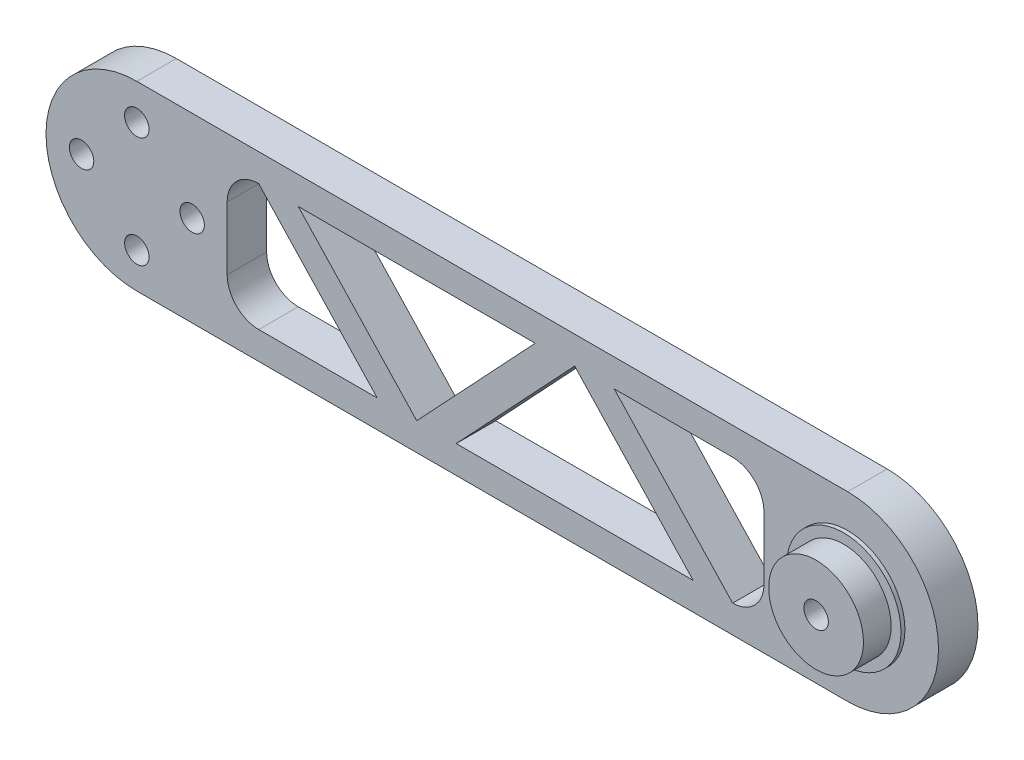
SolidWorks part; units mm, degrees
ref_plane "前视基准面" through (0, 0, 0) normal (0, 0, 1) x (1, 0, 0)
ref_plane "上视基准面" through (0, 0, 0) normal (0, 1, 0) x (1, 0, 0)
ref_plane "右视基准面" through (0, 0, 0) normal (1, 0, 0) x (0, 0, -1)
other "Configuration Table"
sketch "Sketch2" plane through (0, 0, 0) normal (0, 0, 1) x (1, 0, 0)
  line L0 (0, 0) -> (90, 0) construction
  line L1 (0, 11.5) -> (90, 11.5)
  line L2 (0, -11.5) -> (90, -11.5)
  arc A0 (0, 11.5) -> (0, -11.5) centre (0, 0) ccw
  arc A1 (90, -11.5) -> (90, 11.5) centre (90, 0) ccw
  circle A2 centre (90, 0) radius 6
  point P3 (45, 0)
extrude "Boss-Extrude1" add sketch "Sketch2" against normal blind 5 contours L1 A1 L2 A0
sketch "Sketch11" plane through (0, 0, 0) normal (0, 0, 1) x (1, 0, 0)
  circle A0 centre (90, 0) radius 7.25
extrude "Boss-Extrude3" add sketch "Sketch11" along normal blind 0.5 contours A0
sketch "Sketch12" plane through (0, 0, 0.5) normal (0, 0, 1) x (1, 0, 0)
  circle A0 centre (90, 0) radius 6
extrude "Boss-Extrude4" add sketch "Sketch12" along normal blind 3.5 contours A0
sketch "Sketch13" plane through (0, 0, 4) normal (0, 0, 1) x (1, 0, 0)
  circle A0 centre (90, 0) radius 1.55
extrude "Cut-Extrude1" cut sketch "Sketch13" against normal blind 20.5
sketch "Sketch14" plane through (0, 0, -5) normal (0, 0, -1) x (-1, 0, 0)
  line L1 (-93.2136, -0.3551) -> (-91.2993, -2.9606)
  line L2 (-91.2993, -2.9606) -> (-88.0857, -2.6055)
  line L3 (-88.0857, -2.6055) -> (-86.7864, 0.3551)
  line L4 (-86.7864, 0.3551) -> (-88.7007, 2.9606)
  line L5 (-88.7007, 2.9606) -> (-91.9143, 2.6055)
  line L6 (-91.9143, 2.6055) -> (-93.2136, -0.3551)
  circle A0 centre (-90, 0) radius 2.8 construction
extrude "Cut-Extrude2" cut sketch "Sketch14" against normal blind 2.6 contours L4 L5 L6 L1 L2 L3
sketch "Sketch16" plane through (0, 0, -5) normal (0, 0, -1) x (-1, 0, 0)
  circle A0 centre (0, 0) radius 2.85
extrude "Cut-Extrude3" cut sketch "Sketch16" against normal blind 3.02 contours A0
sketch "Sketch17" plane through (0, 0, 0) normal (0, 0, 1) x (1, 0, 0)
  circle A0 centre (0, 7) radius 1.55
  circle A1 centre (0, -7) radius 1.55
  circle A2 centre (-7, 0) radius 1.55
  circle A3 centre (7, 0) radius 1.55
  dimension "D1" = 14
  dimension "D2" = 14
  dimension "D3" = 7
  dimension "D4" = 7
extrude "Cut-Extrude4" cut sketch "Sketch17" against normal blind 10.02 contours A3 | A1 | A2 | A0
sketch "Sketch18" plane through (0, 0, 0) normal (0, 0, 1) x (1, 0, 0)
  line L0 (0, 11.5) -> (90, 11.5) construction
  line L1 (15.4373, 8) -> (75.3963, 8)
  line L2 (11.4373, 4) -> (11.4373, -4)
  line L3 (15.4373, -8) -> (75.4373, -8)
  line L4 (79.3963, 4) -> (79.3963, -4.0002)
  line L5 (0, -11.5) -> (90, -11.5) construction
  line L6 (15.4373, 8) -> (20.4373, 8)
  line L7 (15.4373, 8) -> (30.4373, -8)
  line L8 (20.4373, 8) -> (35.4373, -8)
  line L9 (30.4373, -8) -> (35.4373, -8)
  line L10 (35.4373, -8) -> (40.4373, -8)
  line L11 (35.4373, -8) -> (50.4373, 8)
  line L12 (40.4373, -8) -> (55.4373, 8)
  line L13 (50.4373, 8) -> (55.4373, 8)
  line L22 (55.4373, 8) -> (60.4373, 8)
  line L23 (55.4373, 8) -> (70.4373, -8)
  line L24 (60.4373, 8) -> (75.4373, -8)
  line L25 (70.4373, -8) -> (75.4373, -8)
  arc A0 (75.4373, -8) -> (79.3963, -4.0002) centre (75.3963, -4.0002) ccw
  arc A1 (75.3963, 8) -> (79.3963, 4) centre (75.3963, 4) cw
  arc A2 (11.4373, -4) -> (15.4373, -8) centre (15.4373, -4) ccw
  arc A3 (15.4373, 8) -> (11.4373, 4) centre (15.4373, 4) ccw
  point P16 (50.4373, 8)
  dimension "D1" = 4
  dimension "D2" = 3.5
  dimension "D3" = 3.5
  dimension "D4" = 60
  dimension "D5" = 5
  dimension "D6" = 5
  dimension "D7" = 5
  dimension "D8" = 20
  dimension "D9" = 20
extrude "Cut-Extrude13" cut sketch "Sketch18" against normal blind 10 contours L8 L11 L1 | L7 A3 L2 A2 L3 | L23 L12 L3 | A1 L1 L24 A0 L4
